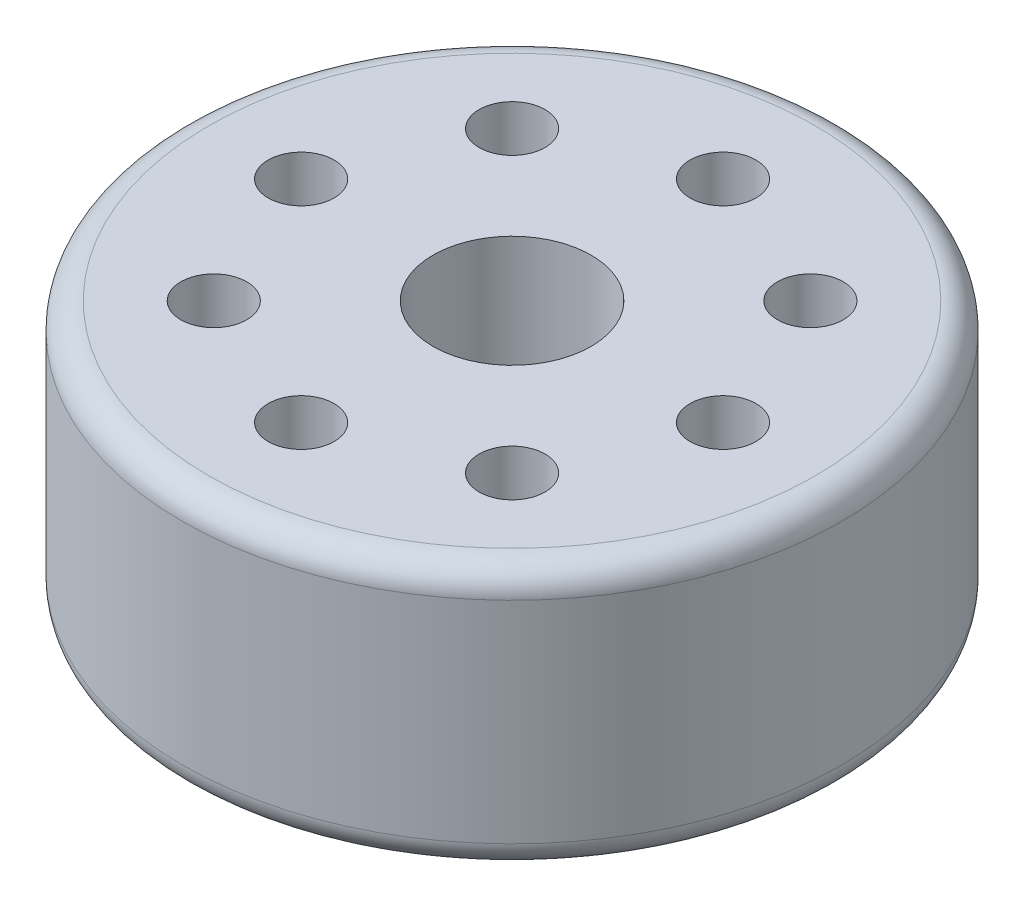
SolidWorks part; units mm, degrees
material "Beryllium Copper, UNS C17000"
ref_plane "Front Plane" through (0, 0, 0) normal (0, 0, 1) x (1, 0, 0)
ref_plane "Top Plane" through (0, 0, 0) normal (0, 1, 0) x (1, 0, 0)
ref_plane "Right Plane" through (0, 0, 0) normal (1, 0, 0) x (0, 0, -1)
sketch "Sketch1" plane through (0, 0, 0) normal (0, 1, 0) x (1, 0, 0)
  line L0 (0, 0) -> (0, 8) construction
  line L1 (0, 0) -> (5.6569, 5.6569) construction
  circle A0 centre (0, 0) radius 12.5
  circle A1 centre (0, 8) radius 1.25
  circle A2 centre (5.6569, 5.6569) radius 1.25
  circle A9 centre (0, 0) radius 3
  circle A10 centre (8, 0) radius 1.25
  circle A11 centre (5.6569, -5.6569) radius 1.25
  circle A12 centre (0, -8) radius 1.25
  circle A13 centre (-5.6569, -5.6569) radius 1.25
  circle A14 centre (-8, 0) radius 1.25
  circle A15 centre (-5.6569, 5.6569) radius 1.25
  point P7 (0, 0)
  point P21 (0, 1.0607)
  point P24 (0, 0)
  dimension "D4" = 25
  dimension "D5" = 2.5
  dimension "D6" = 2.5
  dimension "D8" = 6
  dimension "D1" = 8
  dimension "D2" = 8
  dimension "D3" = 45
  dimension "D7" = 4
extrude "Boss-Extrude1" add sketch "Sketch1" along normal blind 10
fillet "Fillet1" radius 1 2 edges at (0, 0, 12.5) (0, 10, 12.5)
